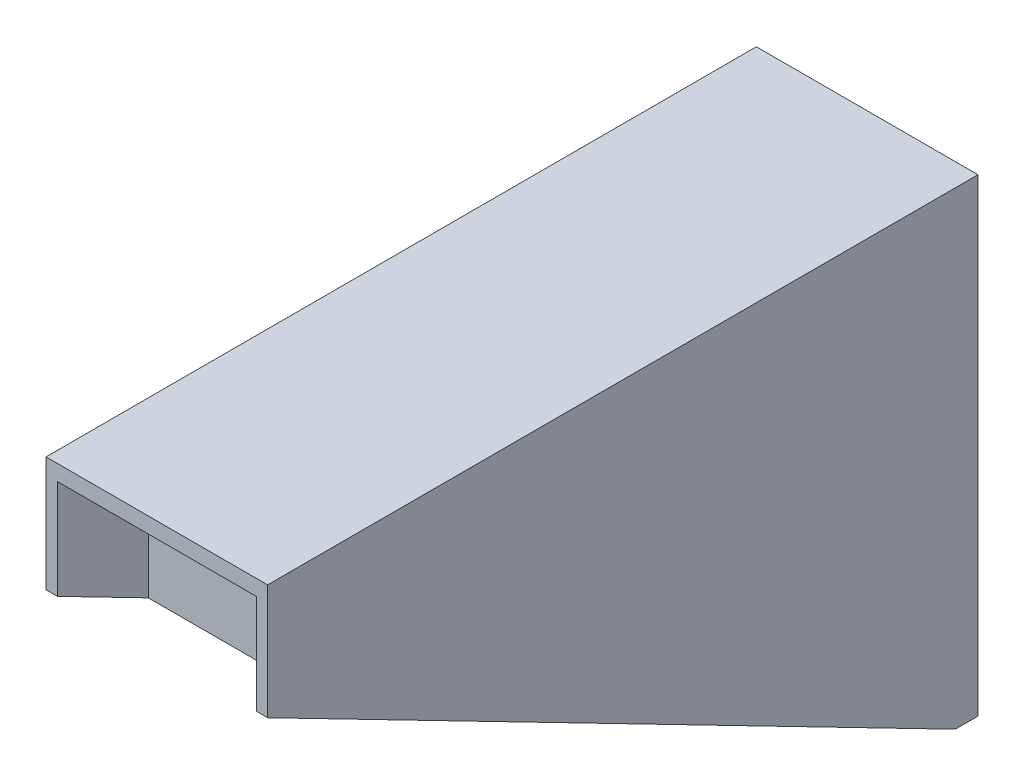
SolidWorks part; units mm, degrees
ref_plane "Plan de face" through (0, 0, 0) normal (0, 0, 1) x (1, 0, 0)
ref_plane "Plan de dessus" through (0, 0, 0) normal (0, 1, 0) x (1, 0, 0)
ref_plane "Plan de droite" through (0, 0, 0) normal (1, 0, 0) x (0, 0, -1)
sketch "Esquisse1" plane through (0, 0, 0) normal (0, 0, 1) x (1, 0, 0)
  line L0 (-79.9333, -38.3784) -> (-79.9333, -203.3784)
  line L1 (-79.9333, -203.3784) -> (-157.9333, -203.3784)
  line L2 (-157.9333, -203.3784) -> (-157.9333, -38.3784)
  line L3 (-157.9333, -38.3784) -> (-79.9333, -38.3784)
extrude "Boss.-Extru.2" add sketch "Esquisse1" along normal blind 250
sketch "Esquisse3" plane through (0, 0, 250) normal (0, 0, 1) x (1, 0, 0)
  line L0 (-157.9333, -38.3784) -> (-157.9333, -203.3784) construction
  line L2 (-153.9333, -43.8784) -> (-153.9333, -203.3784)
  line L3 (-157.9333, -203.3784) -> (-79.9333, -203.3784) construction
  line L4 (-153.9333, -43.8784) -> (-83.9333, -43.8784)
  line L5 (-83.9333, -43.8784) -> (-83.9333, -203.3784)
  line L6 (-79.9333, -203.3784) -> (-79.9333, -38.3784) construction
  line L7 (-79.9333, -38.3784) -> (-157.9333, -38.3784) construction
  dimension "D1" = 4
  dimension "D2" = 4
  dimension "D3" = 5.5
extrude "Enlèv. mat.-Extru.6" cut sketch "Esquisse3" against normal blind 32 and the other way through all
sketch "Esquisse5" plane through (-79.9333, 0, 0) normal (1, 0, 0) x (0, 0, -1)
  line L0 (-250, -78.8784) -> (-8, -203.3784)
  line L1 (-250, -203.3784) -> (-250, -38.3784) construction
  line L2 (-250, -203.3784) -> (0, -203.3784) construction
  dimension "D1" = 40.5
  dimension "D2" = 8
extrude "Enlèv. mat.-Extru.7" cut sketch "Esquisse5" against normal blind 78 and the other way through all flip side to cut
sketch "Esquisse10" plane through (-79.9333, 0, 0) normal (1, 0, 0) x (0, 0, -1)
  line L0 (-250, -43.3784) -> (-215, -43.3784)
  line L1 (-250, -78.8784) -> (-250, -38.3784) construction
  arc A0 (-215, -43.3784) -> (-8, -203.3784) centre (-262.5766, -318.8337) cw
  point P9 (0, 0)
  dimension "D1" = 5
  dimension "D2" = 35
  dimension "D3" = 35
